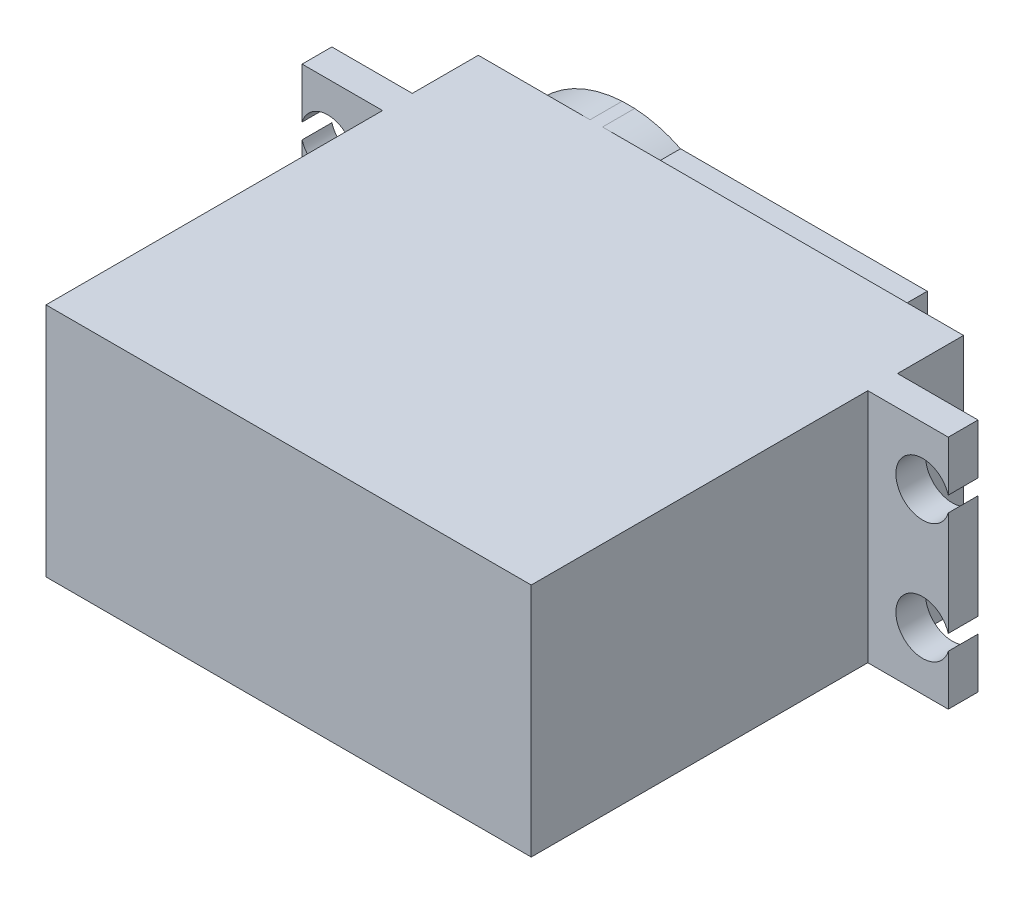
SolidWorks part; units mm, degrees
ref_plane "Front Plane" through (0, 0, 0) normal (0, 0, 1) x (1, 0, 0)
ref_plane "Top Plane" through (0, 0, 0) normal (0, 1, 0) x (1, 0, 0)
ref_plane "Right Plane" through (0, 0, 0) normal (1, 0, 0) x (0, 0, -1)
sketch "Sketch1" plane through (0, 0, 0) normal (0, 1, 0) x (1, 0, 0)
  line L0 (20.4, 18.175) -> (20.4, 12.625) construction
  line L1 (-20.4, -18.175) -> (20.4, -18.175)
  line L2 (-20.4, -18.175) -> (-20.4, 10.125)
  line L3 (-20.4, 18.175) -> (20.4, 18.175)
  line L4 (20.4, -18.175) -> (20.4, 10.125)
  line L5 (-20.4, -18.175) -> (20.4, 18.175) construction
  line L6 (-20.4, 18.175) -> (20.4, -18.175) construction
  line L7 (20.4, 12.625) -> (27.165, 12.625)
  line L8 (27.165, 12.625) -> (27.165, 10.125)
  line L9 (27.165, 10.125) -> (20.4, 10.125)
  line L10 (20.4, 12.625) -> (20.4, 18.175)
  line L11 (0, 18.175) -> (0, -18.175) construction
  line L12 (-27.165, 10.125) -> (-20.4, 10.125)
  line L13 (-27.165, 12.625) -> (-27.165, 10.125)
  line L14 (-20.4, 12.625) -> (-27.165, 12.625)
  line L15 (-20.4, 12.625) -> (-20.4, 18.175)
  point P0 (0, 0)
  dimension "D1" = 36.35
  dimension "D2" = 40.8
  dimension "D3" = 5.55
  dimension "D4" = 6.765
  dimension "D5" = 2.5
extrude "Boss-Extrude1" add sketch "Sketch1" along normal blind 19.812
sketch "Sketch2" plane through (0, 0, -12.625) normal (0, 0, -1) x (-1, 0, 0)
  line L0 (27.165, 0) -> (27.165, 4.87) construction
  line L1 (27.165, 19.812) -> (27.165, 0) construction
  line L2 (27.165, 4.87) -> (25.01, 4.87) construction
  line L3 (20.4, 9.906) -> (28.3858, 9.906) construction
  line L4 (20.4, 19.812) -> (20.4, 0) construction
  line L5 (0, 55) -> (0, -55) construction
  circle A0 centre (25.01, 4.87) radius 2.25
  circle A1 centre (25.01, 14.942) radius 2.25
  circle A2 centre (-25.01, 4.87) radius 2.25
  circle A3 centre (-25.01, 14.942) radius 2.25
  dimension "D3" = 4.5
  dimension "D1" = 4.87
  dimension "D2" = 2.155
extrude "Cut-Extrude1" cut sketch "Sketch2" against normal through all
sketch "Sketch3" plane through (0, 0, -18.175) normal (0, 0, -1) x (-1, 0, 0)
  line L0 (-20.4, 0) -> (-14.65, 0) construction
  line L1 (-20.4, 0) -> (20.4, 0) construction
  line L3 (-14.65, 1.006) -> (6.0986, 1.006)
  line L4 (-14.65, 18.806) -> (6.0986, 18.806)
  line L5 (-20.4, 19.812) -> (-14.65, 19.812) construction
  line L6 (-14.65, 1.006) -> (-14.65, 18.806)
  line L8 (-20.4, 19.812) -> (20.4, 19.812) construction
  line L9 (-14.65, 19.812) -> (-14.65, 20.164) construction
  line L10 (-20.4, 19.812) -> (-20.4, 0) construction
  circle A1 centre (10.48, 9.906) radius 9.92
  point P9 (0, 0)
  point P17 (-14.65, 9.906)
  point P19 (-20.4, 9.906)
  line M8 (-20.4, 0) -> (20.4, 0)
  line M10 (20.4, 19.812) -> (-20.4, 19.812)
  dimension "D1" = 5.75
  dimension "D2" = 20.7486
  dimension "D3" = 17.8
  dimension "D4" = 20.7486
extrude "Boss-Extrude2" add sketch "Sketch3" along normal blind 2.7 contours A1 L4 L6 L3 | A1 M10 M8
sketch "Sketch4" plane through (0, 0, -20.875) normal (0, 0, -1) x (-1, 0, 0)
  circle A1 centre (10.48, 9.906) radius 6.55
  point P2 (0, 0)
  point P3 (0, 0)
  point P8 (0, 0)
  point P11 (0, 0)
  dimension "D1" = 13.1
sketch "Sketch12" plane through (0, 0, -20.875) normal (0, 0, -1) x (-1, 0, 0)
  circle A0 centre (10.48, 9.906) radius 6.55
  dimension "D1" = 13.1
extrude "Boss-Extrude8" add sketch "Sketch12" along normal blind 1.16
sketch "Sketch13" plane through (0, 0, -22.035) normal (0, 0, -1) x (-1, 0, 0)
  circle A0 centre (10.48, 9.906) radius 5.335
  dimension "D1" = 10.67
extrude "Boss-Extrude9" add sketch "Sketch13" along normal blind 0.66
sketch "Sketch14" plane through (0, 0, -22.695) normal (0, 0, -1) x (-1, 0, 0)
  circle A0 centre (10.48, 9.906) radius 2.975
  dimension "D1" = 5.95
extrude "Boss-Extrude11" add sketch "Sketch14" along normal blind 4 contours A0
